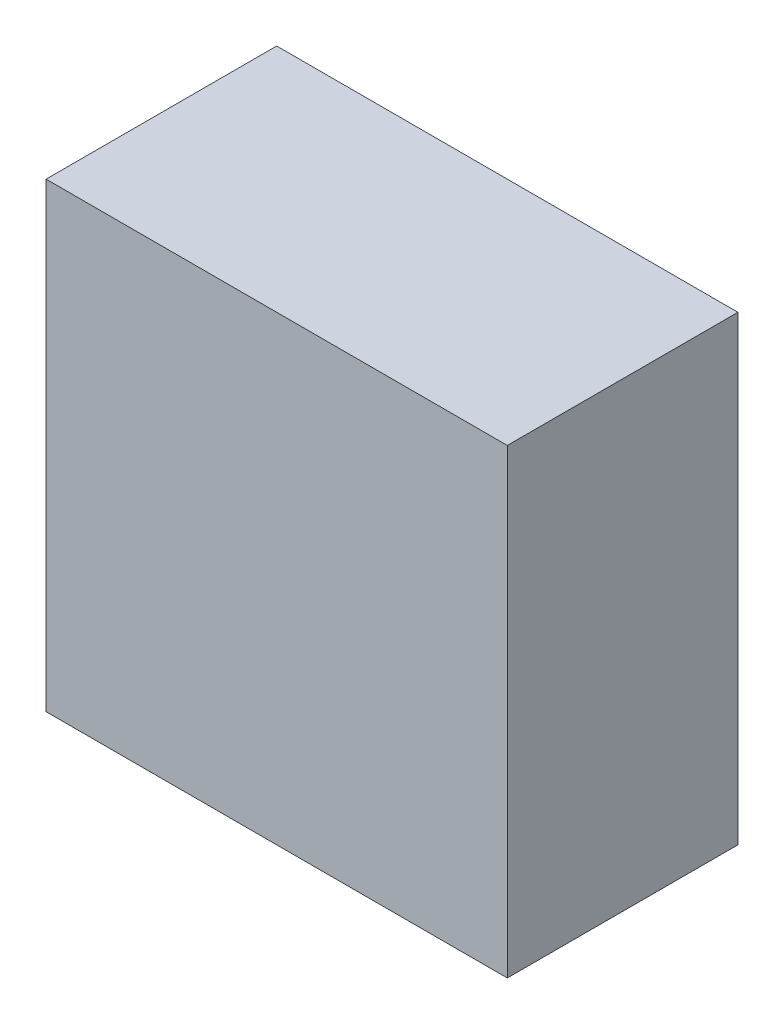
SolidWorks part; units mm, degrees
ref_plane "Front Plane" through (0, 0, 0) normal (0, 0, 1) x (1, 0, 0)
ref_plane "Top Plane" through (0, 0, 0) normal (0, 1, 0) x (1, 0, 0)
ref_plane "Right Plane" through (0, 0, 0) normal (1, 0, 0) x (0, 0, -1)
sketch "Sketch1" plane through (0, 0, 0) normal (0, 0, 1) x (1, 0, 0)
  line L1 (0, 0) -> (20, 0)
  line L2 (0, 0) -> (0, 20)
  line L3 (0, 20) -> (20, 20)
  line L4 (20, 0) -> (20, 20)
  dimension "D1" = 20
extrude "Boss-Extrude1" add sketch "Sketch1" along normal blind 10
